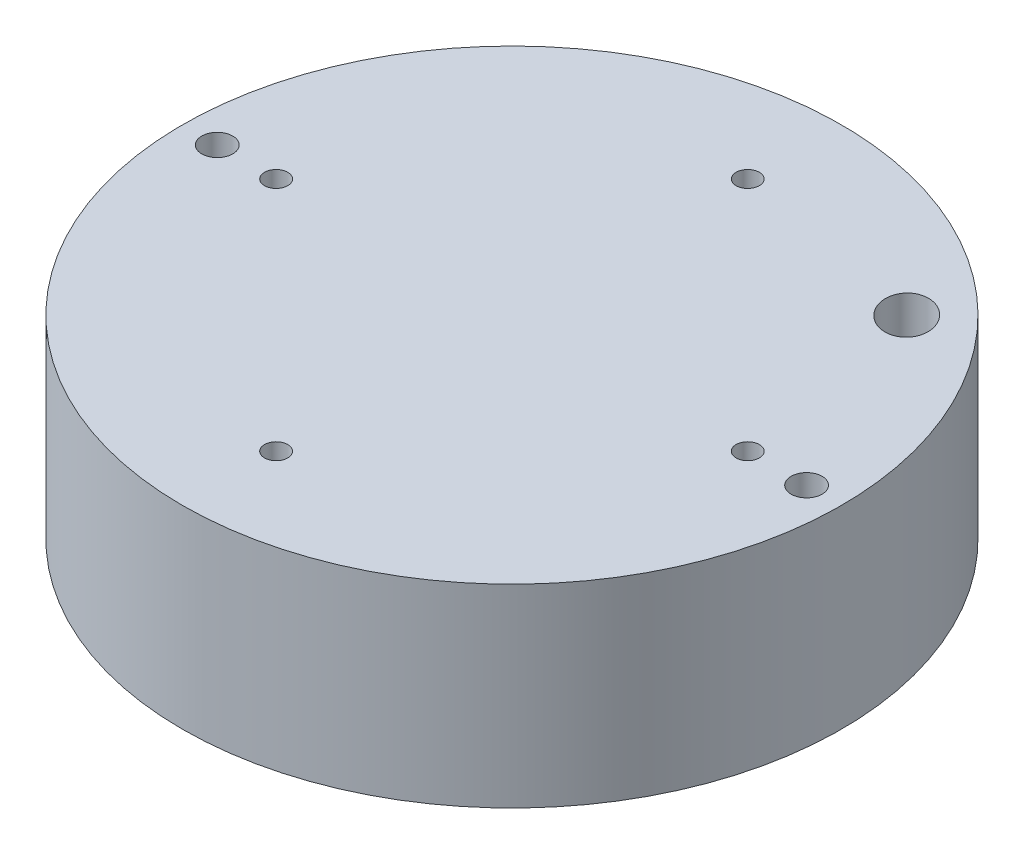
SolidWorks part; units mm, degrees
ref_plane "Alzado" through (0, 0, 0) normal (0, 0, 1) x (1, 0, 0)
ref_plane "Planta" through (0, 0, 0) normal (0, 1, 0) x (1, 0, 0)
ref_plane "Vista lateral" through (0, 0, 0) normal (1, 0, 0) x (0, 0, -1)
sketch "Croquis1" plane through (0, 0, 0) normal (0, 1, 0) x (1, 0, 0)
  circle A0 centre (0, 0) radius 42.5
  dimension "D1" = 85
extrude "Saliente-Extruir1" add sketch "Croquis1" along normal blind 25
sketch "Croquis2" plane through (0, 25, 0) normal (0, 1, 0) x (1, 0, 0)
  line L0 (0, 30.405) -> (0, 0) construction
  line L1 (0, 0) -> (0, -30.405) construction
  line L2 (0, 0) -> (-38, 0) construction
  line L3 (0, 30.405) -> (25.4558, 25.4558) construction
  line L4 (25.4558, 25.4558) -> (30.405, 0) construction
  line L5 (0, 0) -> (25.4558, 25.4558) construction
  circle A1 centre (0, 30.405) radius 1.5
  circle A2 centre (30.405, 0) radius 1.5
  circle A3 centre (0, -30.405) radius 1.5
  circle A4 centre (-30.405, 0) radius 1.5
  circle A5 centre (-38, 0) radius 2
  circle A6 centre (38, 0) radius 2
  ellipse E0 centre (25.4558, 25.4558) end of major axis (27.7814, 22.8401) minor radius 3
  point P16 (0, 0)
  dimension "D1" = 3
  dimension "D5" = 4
  dimension "D3" = 30.405
  dimension "D4" = 38
  dimension "D6" = 36
  dimension "D2" = 4
extrude "Cortar-Extruir1" cut sketch "Croquis2" against normal up to surface (25 mm away) up to face at (0, 0, 42.5)
